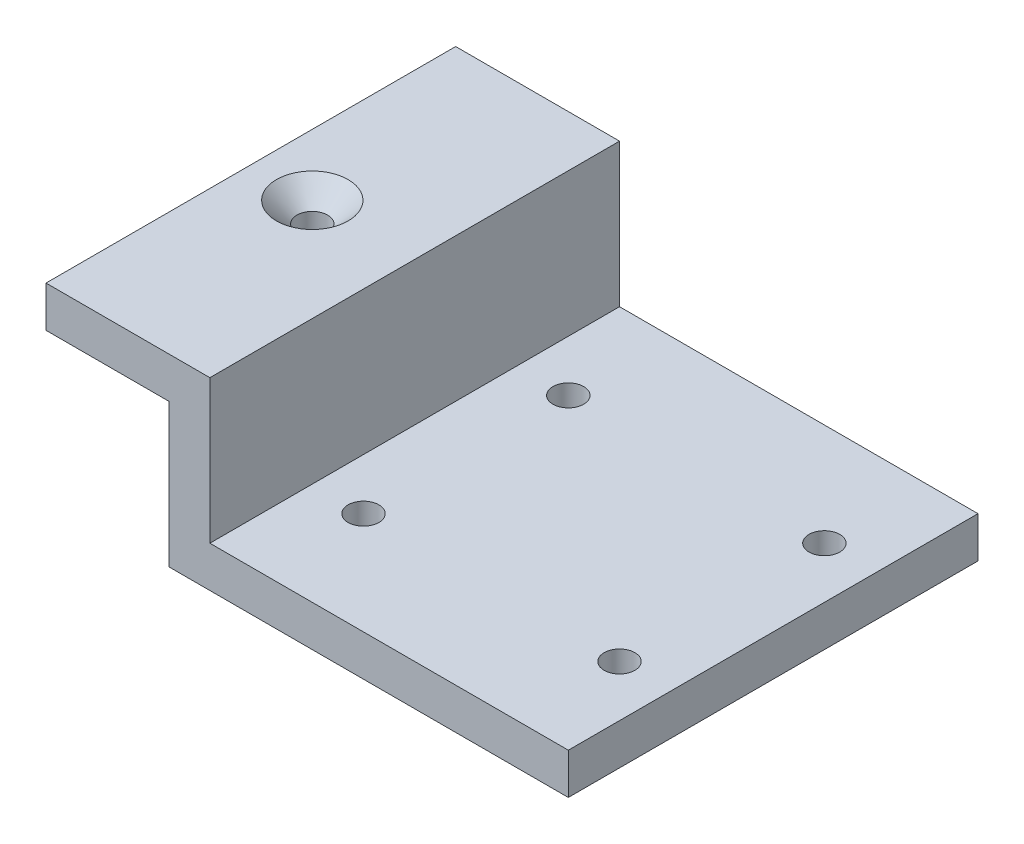
SolidWorks part; units mm, degrees
ref_plane "前视基准面" through (0, 0, 0) normal (0, 0, 1) x (1, 0, 0)
ref_plane "上视基准面" through (0, 0, 0) normal (0, 1, 0) x (1, 0, 0)
ref_plane "右视基准面" through (0, 0, 0) normal (1, 0, 0) x (0, 0, -1)
sketch "草图1" plane through (0, 0, 0) normal (0, 1, 0) x (1, 0, 0)
  line L0 (0, 0) -> (17.5, 0) construction
  line L1 (-17.5, 20) -> (17.5, 20)
  line L2 (-17.5, 20) -> (-17.5, -20)
  line L3 (-17.5, -20) -> (17.5, -20)
  line L4 (17.5, 20) -> (17.5, -20)
  line L5 (0, 0) -> (0, 20) construction
  circle A0 centre (12.5, 10) radius 1.5
  circle A1 centre (-12.5, 10) radius 1.5
  circle A2 centre (-12.5, -10) radius 1.5
  circle A3 centre (12.5, -10) radius 1.5
  dimension "D3" = 3
  dimension "D1" = 40
  dimension "D2" = 35
  dimension "D4" = 25
  dimension "D5" = 20
extrude "凸台-拉伸1" add sketch "草图1" along normal blind 4
sketch "草图2" plane through (-17.5, 0, 0) normal (-1, 0, 0) x (0, 0, 1)
  line L1 (-20, 0) -> (20, 0)
  line L2 (-20, 0) -> (-20, 18)
  line L3 (-20, 18) -> (20, 18)
  line L4 (20, 0) -> (20, 18)
  dimension "D1" = 40
  dimension "D2" = 18
extrude "凸台-拉伸2" add sketch "草图2" along normal blind 4
sketch "草图3" plane through (-21.5, 0, 0) normal (-1, 0, 0) x (0, 0, 1)
  line L0 (20, 0) -> (20, 18) construction
  line L1 (-20, 18) -> (20, 18)
  line L2 (-20, 18) -> (-20, 14)
  line L3 (-20, 14) -> (20, 14)
  line L4 (20, 18) -> (20, 14)
  dimension "D1" = 4
extrude "凸台-拉伸3" add sketch "草图3" along normal blind 12
sketch "草图4" plane through (0, 18, 0) normal (0, 1, 0) x (1, 0, 0)
  line L0 (-33.5, -20) -> (-33.5, 20) construction
  line L1 (-33.5, -20) -> (-17.5, -20) construction
  circle A0 centre (-27.5, 0) radius 1.5
  dimension "D2" = 3
  dimension "D1" = 6
  dimension "D3" = 20
extrude "切除-拉伸1" cut sketch "草图4" against normal up to next
chamfer "倒角1" distance 2 angle 45 1 edges at (-27.5, 18, 1.5)
